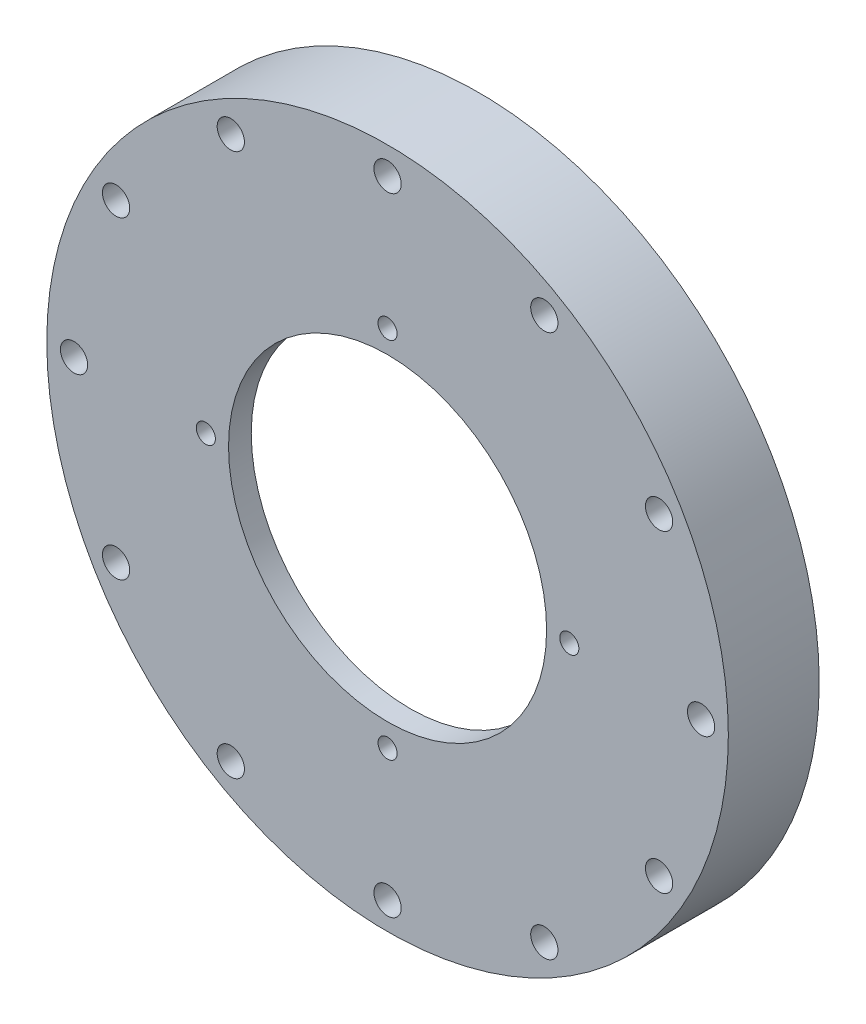
SolidWorks part; units mm, degrees
ref_plane "前视基准面" through (0, 0, 0) normal (0, 0, 1) x (1, 0, 0)
ref_plane "上视基准面" through (0, 0, 0) normal (0, 1, 0) x (1, 0, 0)
ref_plane "右视基准面" through (0, 0, 0) normal (1, 0, 0) x (0, 0, -1)
sketch "草图1" plane through (0, 0, 0) normal (0, 0, 1) x (1, 0, 0)
  circle A0 centre (0, 0) radius 35
  circle A1 centre (0, 0) radius 75
  circle A9 centre (-69, 0) radius 3
  circle A17 centre (-59.7558, 34.5) radius 3
  circle A18 centre (-34.5, 59.7558) radius 3
  circle A19 centre (0, 69) radius 3
  circle A20 centre (34.5, 59.7558) radius 3
  circle A21 centre (59.7558, 34.5) radius 3
  circle A22 centre (69, 0) radius 3
  circle A23 centre (59.7558, -34.5) radius 3
  circle A24 centre (34.5, -59.7558) radius 3
  circle A25 centre (0, -69) radius 3
  circle A26 centre (-34.5, -59.7558) radius 3
  circle A27 centre (-59.7558, -34.5) radius 3
  point P25 (-0.25, 0)
  point P32 (0, 0)
  point P36 (0, 0)
  dimension "D1" = 12
extrude "凸台-拉伸1" add sketch "草图1" along normal blind 20
sketch "草图2" plane through (0, 0, 0) normal (0, 0, 1) x (1, 0, 0)
  circle A0 centre (0, 0) radius 60
extrude "切除-拉伸1" cut sketch "草图2" along normal blind 15
sketch "草图6" plane through (0, 0, 0) normal (0, 0, 1) x (1, 0, 0)
  line L0 (0, 0) -> (40, 0)
  line L1 (0, 0) -> (0, 40)
  line L2 (0, 0) -> (-40, 0)
  line L3 (0, 0) -> (0, -40)
hole_wizard "M5 螺纹孔的螺纹孔钻头2" positions "草图10" profile "草图11" hole size "M5" standard "GB" end condition through all
sketch "草图10" plane through (0, 0, 20) normal (0, 0, 1) x (1, 0, 0)
  line L0 (0, -40) -> (0, 0) construction
  line L1 (0, 0) -> (40, 0) construction
  point P0 (0, 40)
  point P3 (40, 0)
  point P6 (0, -40)
  point P9 (-40, 0)
sketch "草图11" plane through (0, 40, 20) normal (1, 0, 0) x (0, -1, 0)
  line L0 (0, 0) -> (0, 20)
  line L1 (0, 20) -> (2.1, 20)
  line L2 (2.1, 20) -> (2.1, 0)
  line L5 (2.1, 0) -> (0, 0)
  line L11 (0, -6.35) -> (0, 107.95) construction
  dimension "通孔孔直径" = 4.2
  dimension "通孔孔深度" = 20
cosmetic thread "装饰螺纹线1" parameters "D2"=5
